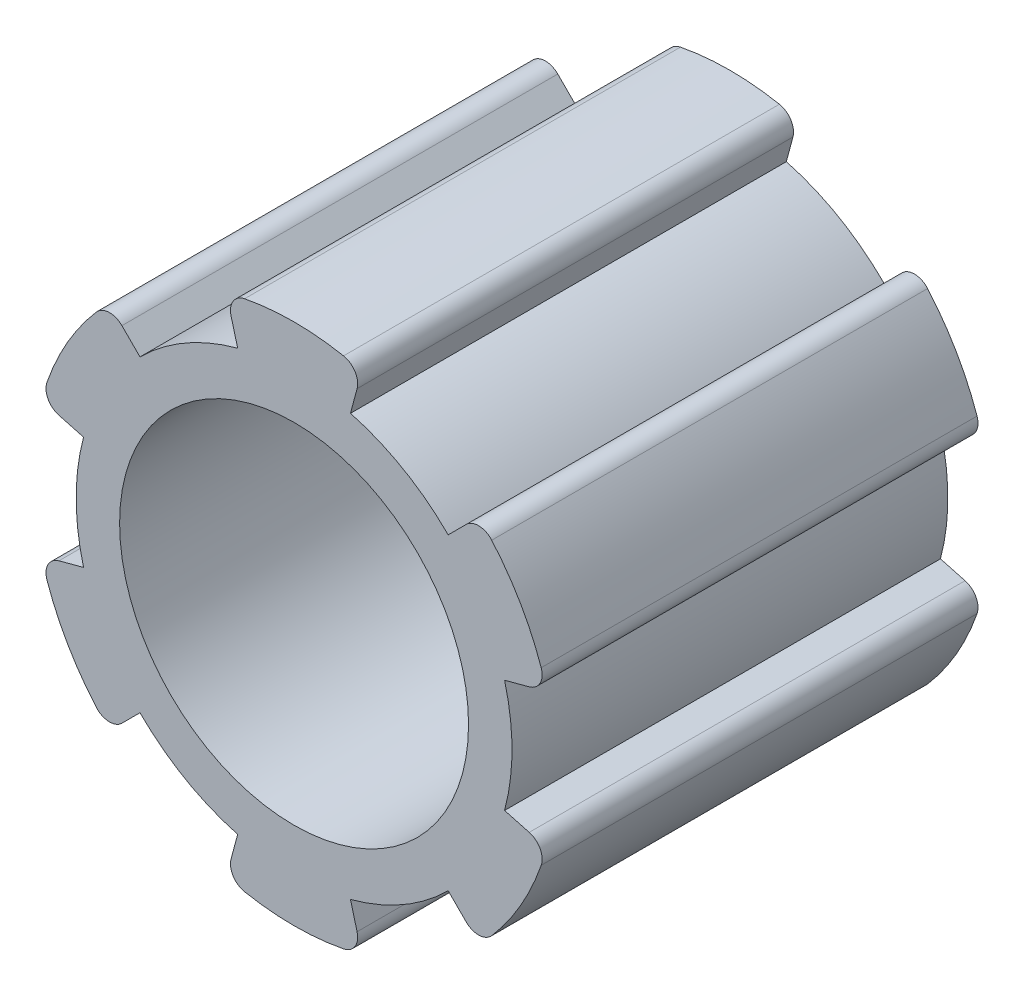
SolidWorks part; units mm, degrees
ref_plane "Front Plane" through (0, 0, 0) normal (0, 0, 1) x (1, 0, 0)
ref_plane "Top Plane" through (0, 0, 0) normal (0, 1, 0) x (1, 0, 0)
ref_plane "Right Plane" through (0, 0, 0) normal (1, 0, 0) x (0, 0, -1)
sketch "Sketch1" plane through (0, 0, 0) normal (0, 0, 1) x (1, 0, 0)
  circle A0 centre (0, 0) radius 20.015
  circle A1 centre (0, 0) radius 25
  dimension "D1" = 50
  dimension "D2" = 40.03
extrude "Boss-Extrude1" add sketch "Sketch1" against normal blind 50
sketch "Sketch2" plane through (0, 0, 0) normal (0, 0, 1) x (1, 0, 0)
  line L0 (0, 0) -> (0, 25) construction
  line L2 (6.4705, 24.1481) -> (7.7646, 28.9778)
  line L3 (-258.819, -965.9258) -> (12682.1332, 47330.3655) construction
  line L4 (-6.4705, 24.1481) -> (-7.7646, 28.9778)
  line L5 (0, 30) -> (0, 18.4002) construction
  arc A0 (6.4705, 24.1481) -> (-6.4705, 24.1481) centre (0, 0) ccw
  arc A1 (7.7646, 28.9778) -> (-7.7646, 28.9778) centre (0, 0) ccw
  dimension "D1" = 50
  dimension "D2" = 60
  dimension "D3" = 30
extrude "Boss-Extrude2" add sketch "Sketch2" against normal up to surface (50 mm away) up to face at (20.015, 0, -50)
fillet "Fillet1" radius 2 2 edges at (7.7646, 28.9778, -25) (-7.7646, 28.9778, -25)
pattern_circular "CirPattern1" count 6 every 60 about axis through (0, 0, 0) along (0, 0, 1) of "Boss-Extrude2", "Fillet1"
